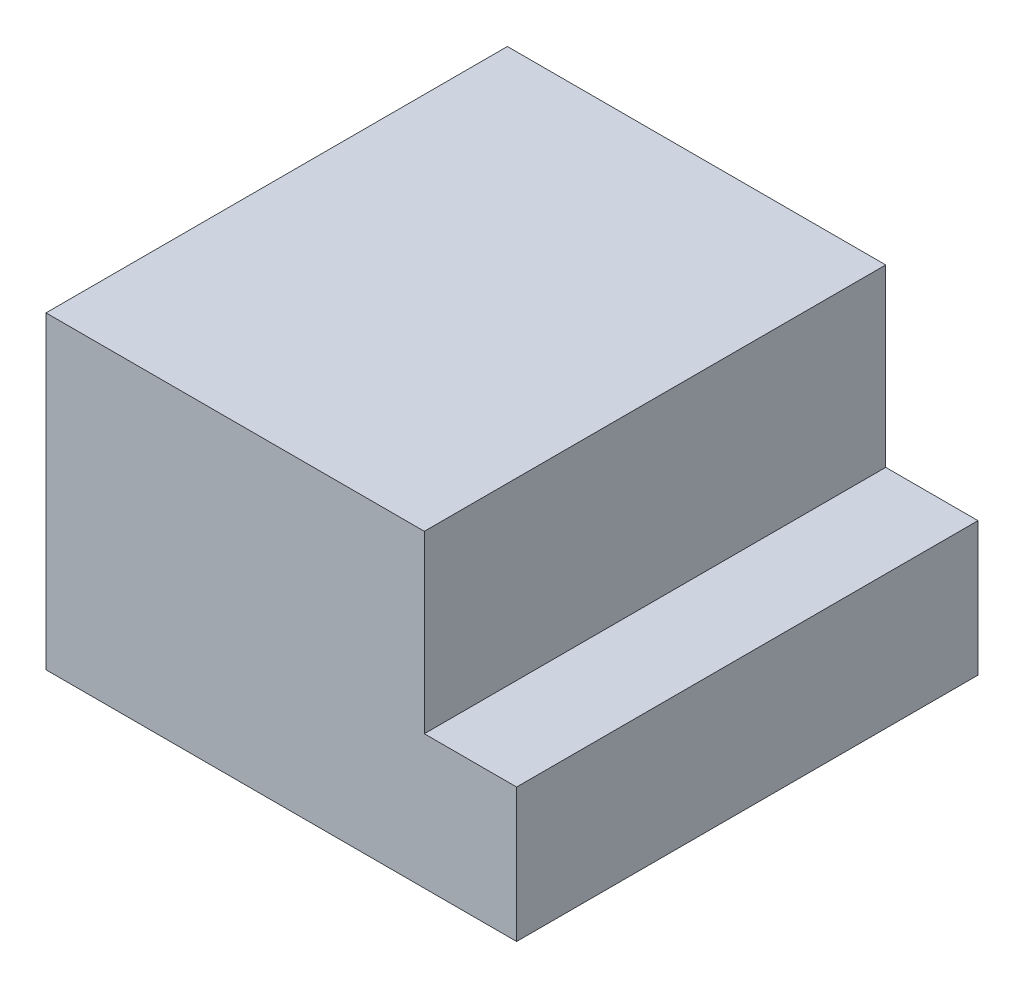
SolidWorks part; units mm, degrees
ref_plane "前视基准面" through (0, 0, 0) normal (0, 0, 1) x (1, 0, 0)
ref_plane "上视基准面" through (0, 0, 0) normal (0, 1, 0) x (1, 0, 0)
ref_plane "右视基准面" through (0, 0, 0) normal (1, 0, 0) x (0, 0, -1)
sketch "草图1" plane through (0, 0, 0) normal (1, 0, 0) x (0, 0, -1)
  line L1 (-50, -33.5) -> (50, -33.5)
  line L2 (-50, -33.5) -> (-50, 33.5)
  line L3 (-50, 33.5) -> (50, 33.5)
  line L4 (50, -33.5) -> (50, 33.5)
  line L5 (-50, -33.5) -> (50, 33.5) construction
  line L6 (-50, 33.5) -> (50, -33.5) construction
  point P0 (0, 0)
  dimension "D1" = 67
  dimension "D2" = 67
  dimension "D3" = 100
extrude "凸台-拉伸1" add sketch "草图1" along normal mid plane 82
sketch "草图2" plane through (41, 0, 0) normal (1, 0, 0) x (0, 0, -1)
  line L0 (-50, -33.5) -> (50, -33.5) construction
  line L1 (-50, -33.5) -> (50, -33.5)
  line L2 (-50, -33.5) -> (-50, -4.5)
  line L3 (-50, 33.5) -> (-50, -33.5) construction
  line L4 (-50, -4.5) -> (50, -4.5)
  line L5 (50, -33.5) -> (50, 33.5) construction
  line L6 (50, -4.5) -> (50, -33.5)
  dimension "D1" = 29
extrude "凸台-拉伸2" add sketch "草图2" along normal blind 20
